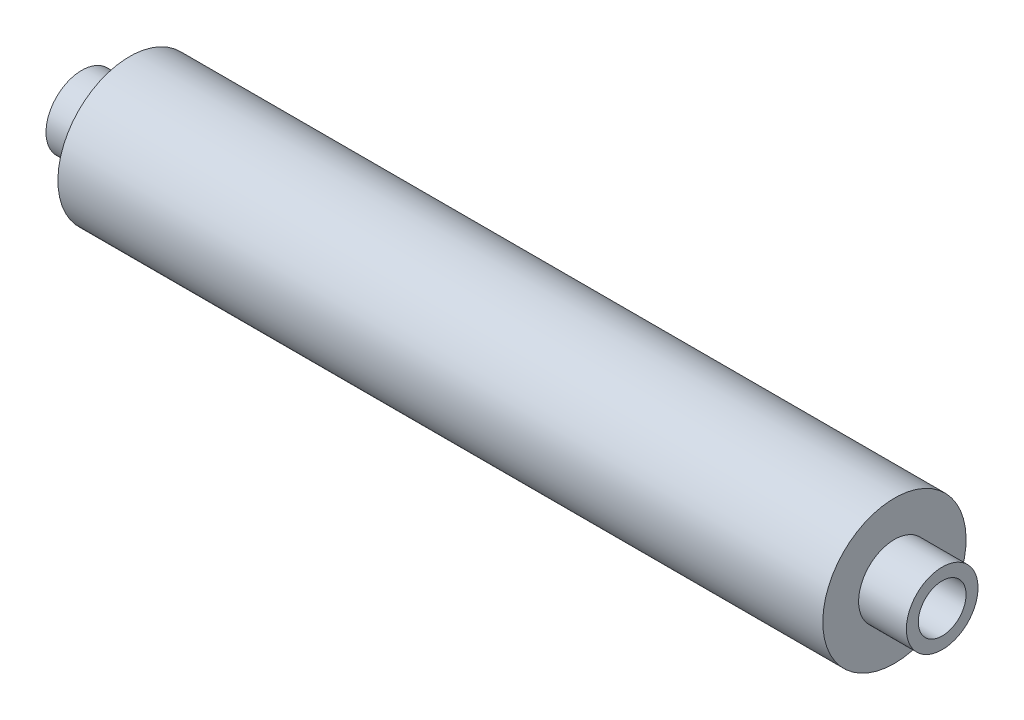
SolidWorks part; units mm, degrees
ref_plane "Alzado" through (0, 0, 0) normal (0, 0, 1) x (1, 0, 0)
ref_plane "Planta" through (0, 0, 0) normal (0, 1, 0) x (1, 0, 0)
ref_plane "Vista lateral" through (0, 0, 0) normal (1, 0, 0) x (0, 0, -1)
sketch "Sketch1" plane through (0, 0, 0) normal (0, 0, 1) x (1, 0, 0)
  line L0 (-45.033, 0) -> (45.033, 0)
  line L1 (45.033, 0) -> (45.033, 3.75)
  line L2 (45.033, 3.75) -> (40.033, 3.75)
  line L3 (40.033, 3.75) -> (40.033, 7.5)
  line L4 (40.033, 7.5) -> (-40.033, 7.5)
  line L5 (-40.033, 7.5) -> (-40.033, 3.75)
  line L6 (-40.033, 3.75) -> (-45.033, 3.75)
  line L7 (-45.033, 3.75) -> (-45.033, 0)
  point P4 (0, 0)
  dimension "D1" = 80.066
  dimension "D2" = 3.75
  dimension "D3" = 5
  dimension "D4" = 7.5
revolve "Revolve1" add sketch "Sketch1" angle 360 about L0
sketch "Sketch2" plane through (45.033, 0, 0) normal (1, 0, 0) x (0, 0, -1)
  circle A0 centre (0, 0) radius 2.5
extrude "Cut-Extrude1" cut sketch "Sketch2" against normal blind 20
mirror "Mirror1" about plane through (0, 0, 0) normal (1, 0, 0) of "Cut-Extrude1"
